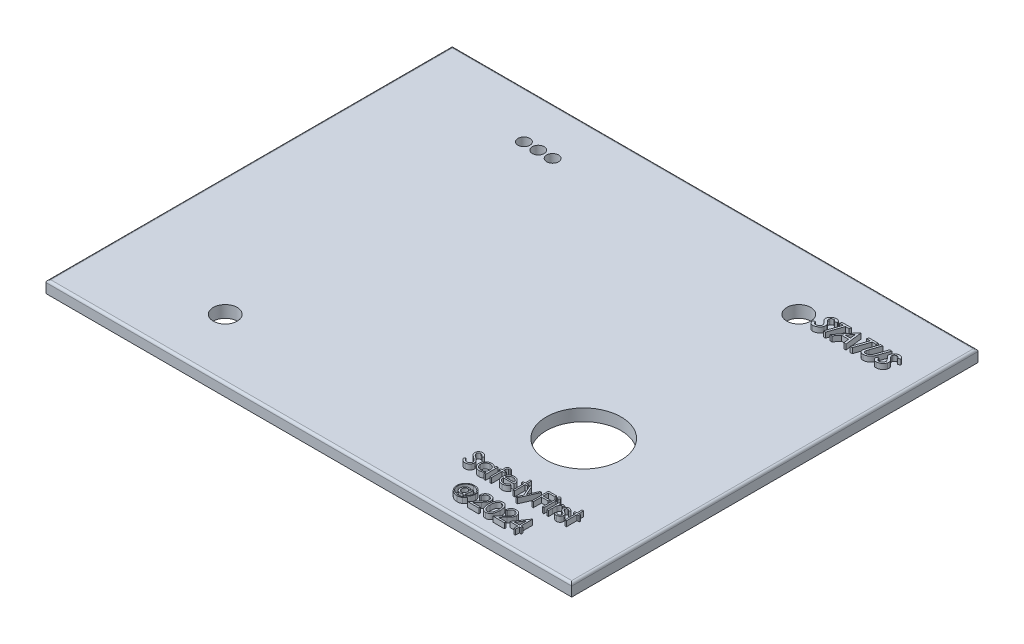
SolidWorks part; units mm, degrees
ref_plane "Front Plane" through (0, 0, 0) normal (0, 0, 1) x (1, 0, 0)
ref_plane "Top Plane" through (0, 0, 0) normal (0, 1, 0) x (1, 0, 0)
ref_plane "Right Plane" through (0, 0, 0) normal (1, 0, 0) x (0, 0, -1)
sketch "Sketch1" plane through (0, 0, 0) normal (0, 1, 0) x (1, 0, 0)
  line L1 (-55, -42.5) -> (55, -42.5)
  line L2 (-55, -42.5) -> (-55, 42.5)
  line L3 (-55, 42.5) -> (55, 42.5)
  line L4 (55, -42.5) -> (55, 42.5)
  line L5 (-55, -42.5) -> (55, 42.5) construction
  line L6 (-55, 42.5) -> (55, -42.5) construction
  point P0 (0, 0)
  dimension "D1" = 110
  dimension "D2" = 85
extrude "Boss-Extrude1" add sketch "Sketch1" along normal blind 2.5
sketch "Sketch2" plane through (0, 2.5, 0) normal (0, 1, 0) x (1, 0, 0)
  line L0 (-30, -42.5) -> (-30, -30) construction
  line L1 (-55, -42.5) -> (55, -42.5) construction
  line L2 (-30, -30) -> (-55, -30) construction
  line L3 (-55, 42.5) -> (-55, -42.5) construction
  circle A0 centre (-30, -30) radius 2.5
  dimension "D3" = 5
  dimension "D1" = 12.5
  dimension "D2" = 25
extrude "Cut-Extrude2" cut sketch "Sketch2" against normal blind 10
sketch "Sketch3" plane through (0, 2.5, 0) normal (0, 1, 0) x (1, 0, 0)
  line L0 (-30, 42.5) -> (-30, 32.5) construction
  line L1 (55, 42.5) -> (-55, 42.5) construction
  line L2 (-30, 32.5) -> (-55, 32.5) construction
  line L3 (-55, 42.5) -> (-55, -42.5) construction
  circle A0 centre (-30, 32.5) radius 1.25
  circle A1 centre (-27, 32.5) radius 1.25
  circle A2 centre (-24, 32.5) radius 1.25
  dimension "D3" = 2.5
  dimension "D4" = 3
  dimension "D1" = 10
  dimension "D2" = 25
extrude "Cut-Extrude3" cut sketch "Sketch3" against normal blind 10
sketch "Sketch4" plane through (0, 2.5, 0) normal (0, 1, 0) x (1, 0, 0)
  line L0 (55, -15) -> (30, -15) construction
  line L1 (55, -42.5) -> (55, 42.5) construction
  line L2 (30, -15) -> (30, -42.5) construction
  line L3 (-55, -42.5) -> (55, -42.5) construction
  circle A0 centre (30, -15) radius 7.825
  dimension "D3" = 15.65
  dimension "D1" = 25
  dimension "D2" = 27.5
extrude "Cut-Extrude4" cut sketch "Sketch4" against normal blind 10
sketch "Sketch5" plane through (0, 2.5, 0) normal (0, 1, 0) x (1, 0, 0)
  line L0 (30, -15) -> (30, 42.5) construction
  line L1 (55, 42.5) -> (-55, 42.5) construction
  line L2 (55, 30) -> (30, 30) construction
  line L3 (55, -42.5) -> (55, 42.5) construction
  circle A0 centre (30, 30) radius 2.5
  dimension "D2" = 5
  dimension "D1" = 12.5
extrude "Cut-Extrude5" cut sketch "Sketch5" against normal blind 10
sketch "Sketch6" plane through (0, 2.5, 0) normal (0, 1, 0) x (1, 0, 0)
  line L0 (30, 30) -> (30, 17.9033) construction
  text T0 "<b><i>STATUS</i></b>\r\n"
extrude "Boss-Extrude3" add sketch "Sketch6" along normal blind 1.1
sketch "Sketch7" plane through (0, 2.5, 0) normal (0, 1, 0) x (1, 0, 0)
  text T0 "SafetyFirst\r\n   @2024"
extrude "Boss-Extrude5" add sketch "Sketch7" along normal blind 1.1
fillet "Fillet2" radius 0.5 4 edges at (0, 2.5, 42.5) (55, 2.5, 0) (0, 2.5, -42.5) (-55, 2.5, 0)
